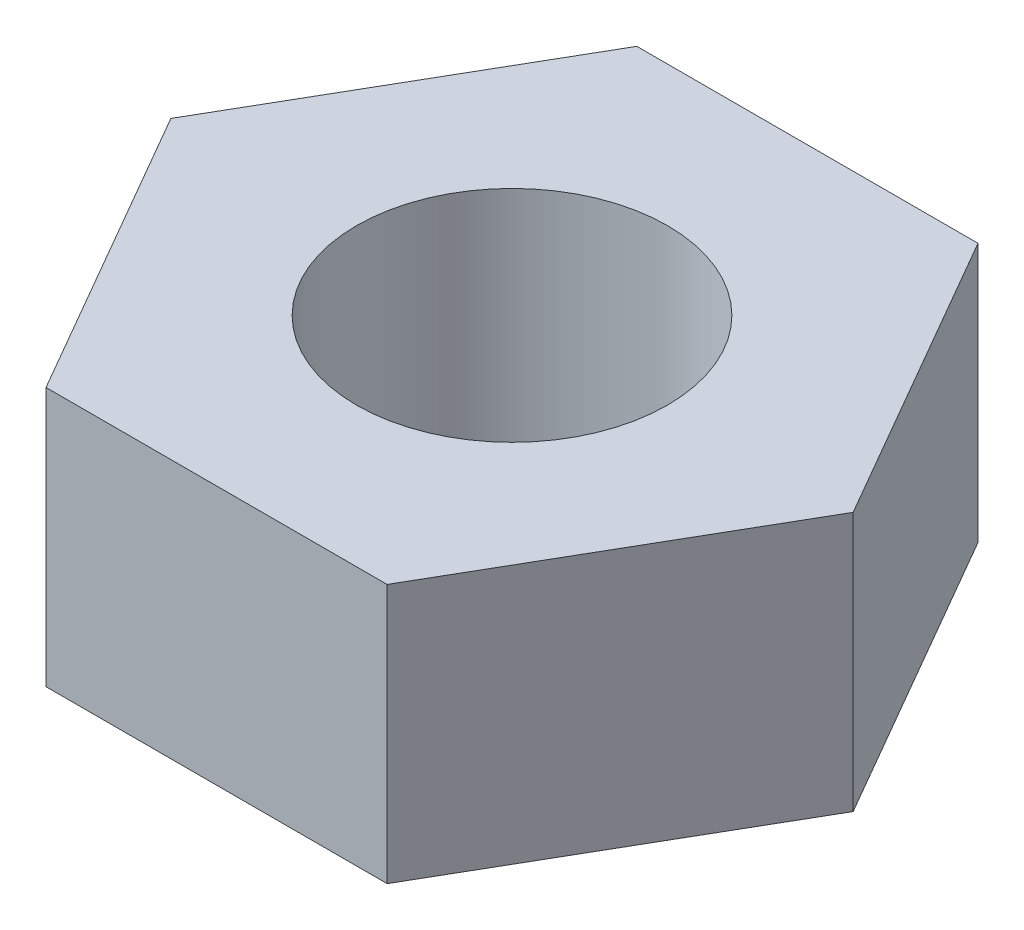
SolidWorks part; units mm, degrees
ref_plane "Front Plane" through (0, 0, 0) normal (0, 0, 1) x (1, 0, 0)
ref_plane "Top Plane" through (0, 0, 0) normal (0, 1, 0) x (1, 0, 0)
ref_plane "Right Plane" through (0, 0, 0) normal (1, 0, 0) x (0, 0, -1)
sketch "Sketch1" plane through (0, 0, 0) normal (0, 1, 0) x (1, 0, 0)
  line L1 (3.2909, 0) -> (1.6454, 2.85)
  line L2 (1.6454, 2.85) -> (-1.6454, 2.85)
  line L3 (-1.6454, 2.85) -> (-3.2909, 0)
  line L4 (-3.2909, 0) -> (-1.6454, -2.85)
  line L5 (-1.6454, -2.85) -> (1.6454, -2.85)
  line L6 (1.6454, -2.85) -> (3.2909, 0)
  circle A0 centre (0, 0) radius 1.5
  circle A1 centre (0, 0) radius 2.85 construction
  dimension "D1" = 3
  dimension "D2" = 5.7
extrude "Thickness" add sketch "Sketch1" along normal blind 2.5
